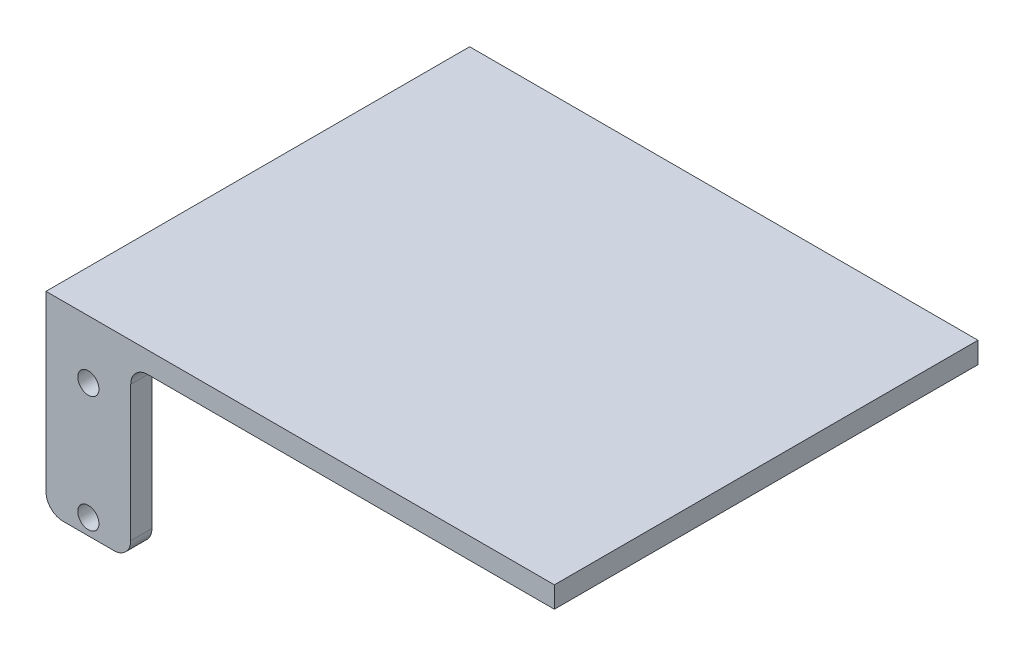
SolidWorks part; units mm, degrees
ref_plane "Front Plane" through (0, 0, 0) normal (0, 0, 1) x (1, 0, 0)
ref_plane "Top Plane" through (0, 0, 0) normal (0, 1, 0) x (1, 0, 0)
ref_plane "Right Plane" through (0, 0, 0) normal (1, 0, 0) x (0, 0, -1)
sketch "Sketch1" plane through (0, 0, 0) normal (0, 1, 0) x (1, 0, 0)
  line L1 (38.1, -31.75) -> (-38.1, -31.75)
  line L2 (38.1, -31.75) -> (38.1, 31.75)
  line L3 (38.1, 31.75) -> (-38.1, 31.75)
  line L4 (-38.1, -31.75) -> (-38.1, 31.75)
  line L5 (38.1, -31.75) -> (-38.1, 31.75) construction
  line L6 (38.1, 31.75) -> (-38.1, -31.75) construction
  point P0 (0, 0)
  dimension "D1" = 63.5
  dimension "D2" = 76.2
extrude "Boss-Extrude1" add sketch "Sketch1" against normal blind 3.175
sketch "Sketch3" plane through (0, 0, 31.75) normal (0, 0, 1) x (1, 0, 0)
  line L0 (-31.75, -8.7312) -> (-31.75, -26.1937) construction
  line L1 (-38.1, -3.175) -> (-25.4, -3.175)
  line L2 (-38.1, -3.175) -> (-38.1, -28.575)
  line L3 (-38.1, -28.575) -> (-25.4, -28.575)
  line L4 (-25.4, -3.175) -> (-25.4, -28.575)
  line L5 (-31.75, -17.4625) -> (-38.1, -17.4625) construction
  circle A0 centre (-31.75, -26.1937) radius 1.5875
  circle A1 centre (-31.75, -8.7312) radius 1.5875
  point P11 (-32.398, -14.2875)
  point P12 (-31.75, -28.575)
  point P13 (-38.1, -17.5546)
  point P14 (-38.1, -15.875)
  dimension "D3" = 3.175
  dimension "D4" = 17.4625
  dimension "D1" = 25.4
  dimension "D2" = 12.7
  dimension "D5" = 1.5875
extrude "Boss-Extrude2" add sketch "Sketch3" against normal blind 3.175
mirror "Mirror1" about plane through (0, 0, 0) normal (0, 0, 1) of "Boss-Extrude2"
fillet "Fillet1" radius 2.54 6 edges at (-25.4, -3.175, 30.1625) (-25.4, -3.175, -30.1625) (-25.4, -28.575, -30.1625) (-38.1, -28.575, -30.1625) (-25.4, -28.575, 30.1625) (-38.1, -28.575, 30.1625)
